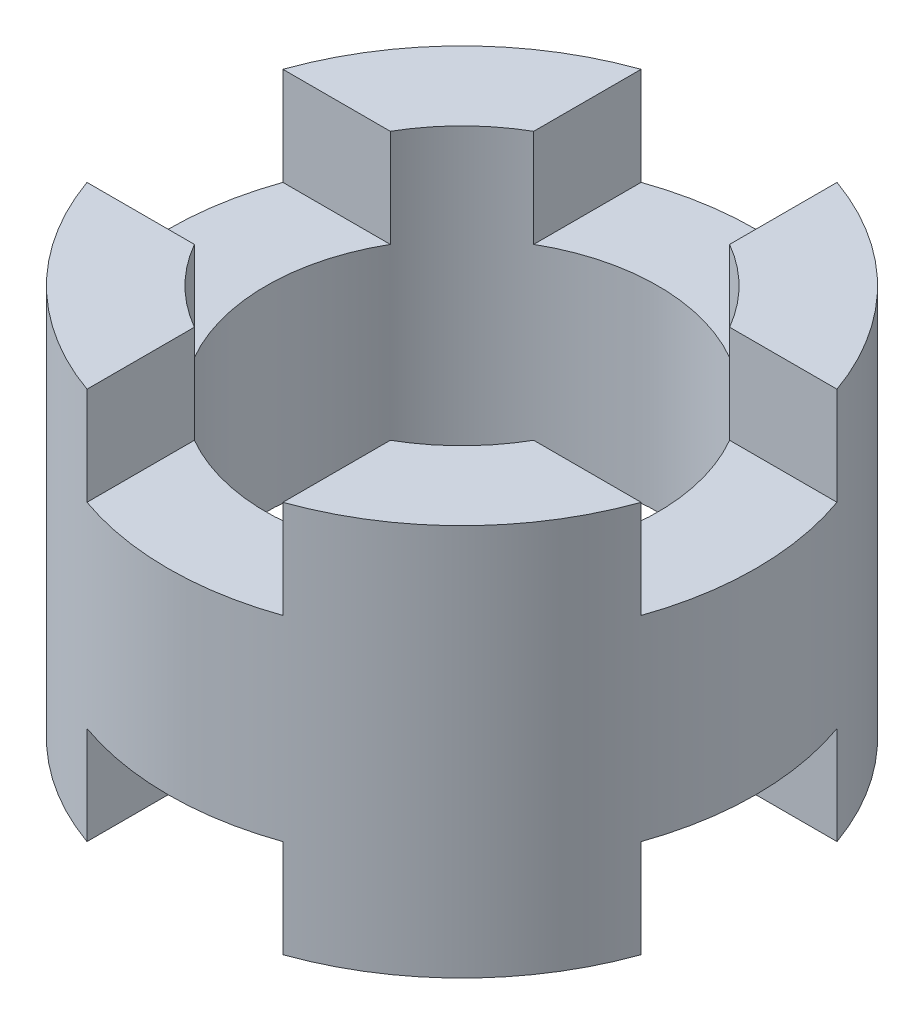
SolidWorks part; units mm, degrees
ref_plane "Front Plane" through (0, 0, 0) normal (0, 0, 1) x (1, 0, 0)
ref_plane "Top Plane" through (0, 0, 0) normal (0, 1, 0) x (1, 0, 0)
ref_plane "Right Plane" through (0, 0, 0) normal (1, 0, 0) x (0, 0, -1)
sketch "Sketch2" plane through (0, 0, 0) normal (0, 1, 0) x (1, 0, 0)
  circle A0 centre (0, 0) radius 19.05
  circle A1 centre (0, 0) radius 12.7
  dimension "D1" = 6.35
  dimension "D2" = 25.4
  dimension "D3" = 38.1
extrude "Boss-Extrude2" add sketch "Sketch2" along normal blind 25.4 contours A0 | A1
sketch "Sketch4" plane through (0, 25.4, 0) normal (0, 1, 0) x (1, 0, 0)
  line L1 (38.1, 6.35) -> (-38.1, 6.35)
  line L2 (38.1, 6.35) -> (38.1, -6.35)
  line L3 (38.1, -6.35) -> (-38.1, -6.35)
  line L4 (-38.1, 6.35) -> (-38.1, -6.35)
  line L5 (0, -6.35) -> (0, 6.35) construction
  line L6 (38.1, 0) -> (-38.1, 0) construction
  point P0 (0, 0)
  dimension "D1" = 12.7
extrude "Cut-Extrude7" cut sketch "Sketch4" against normal blind 6.35
pattern_circular "CirPattern1" count 2 every 90 about axis through (0, 25.4, 0) along (0, 1, 0) of "Cut-Extrude7"
sketch "Sketch8" plane through (0, 0, 0) normal (0, -1, 0) x (1, 0, 0)
  line L5 (-39.198, -6.35) -> (39.198, -6.35)
  line L6 (-39.198, -6.35) -> (-39.198, 6.35)
  line L7 (-39.198, 6.35) -> (39.198, 6.35)
  line L8 (39.198, -6.35) -> (39.198, 6.35)
  line L9 (0, 6.35) -> (0, -6.35) construction
  line L10 (-39.198, 0) -> (39.198, 0) construction
  point P0 (0, 0)
  point P1 (0, 0)
  point P5 (39.198, 0)
  dimension "D1" = 12.7
extrude "Cut-Extrude9" cut sketch "Sketch8" against normal blind 6.35
pattern_circular "CirPattern2" count 2 every 90 about axis through (0, 25.4, 0) along (0, -1, 0) of "Cut-Extrude9"
equation "\"D1@Sketch4\"=\"D1@Sketch8\""
